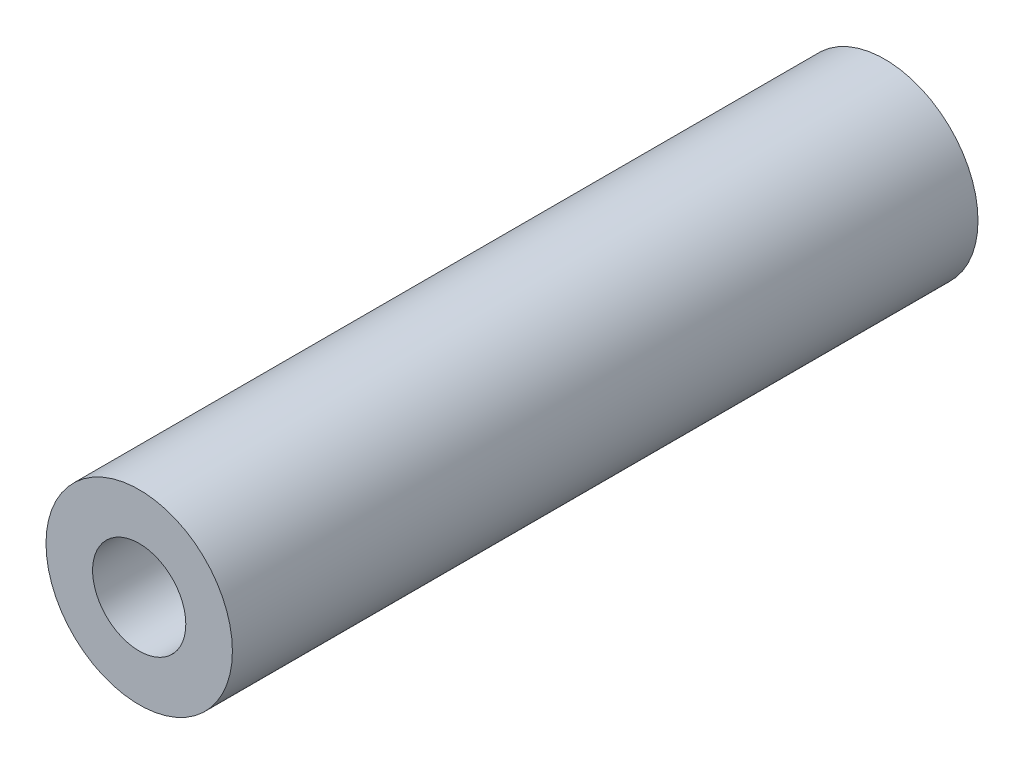
SolidWorks part; units mm, degrees
ref_plane "Front Plane" through (0, 0, 0) normal (0, 0, 1) x (1, 0, 0)
ref_plane "Top Plane" through (0, 0, 0) normal (0, 1, 0) x (1, 0, 0)
ref_plane "Right Plane" through (0, 0, 0) normal (1, 0, 0) x (0, 0, -1)
sketch "Sketch1" plane through (0, 0, 0) normal (0, 0, 1) x (1, 0, 0)
  circle A0 centre (0, 0) radius 25.4
  circle A1 centre (0, 0) radius 12.7
  dimension "D1" = 50.8
  dimension "D2" = 25.4
extrude "Boss-Extrude1" add sketch "Sketch1" along normal blind 203.2
